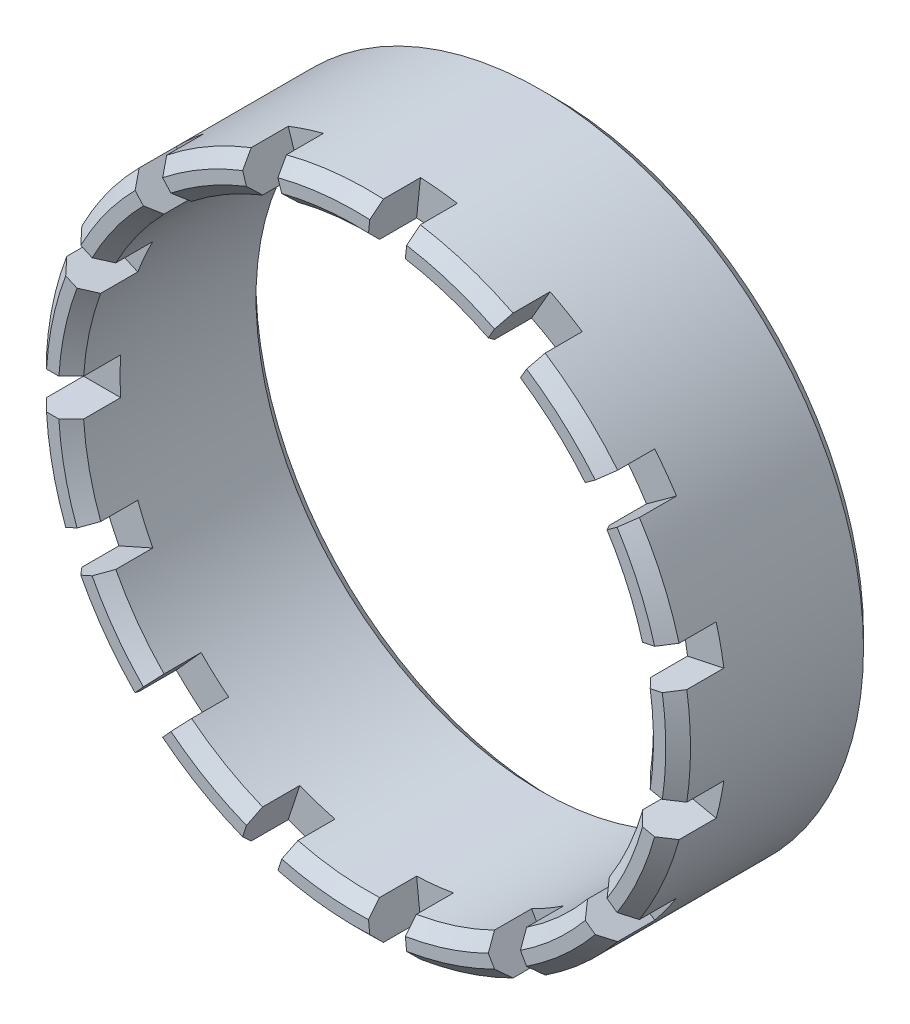
SolidWorks part; units mm, degrees
material "PET"
ref_plane "Front Plane" through (0, 0, 0) normal (0, 0, 1) x (1, 0, 0)
ref_plane "Top Plane" through (0, 0, 0) normal (0, 1, 0) x (1, 0, 0)
ref_plane "Right Plane" through (0, 0, 0) normal (1, 0, 0) x (0, 0, -1)
sketch "Sketch1" plane through (0, 0, 0) normal (0, 0, 1) x (1, 0, 0)
  circle A1 centre (0, 0) radius 36.6395
  circle A2 centre (0, 0) radius 41.402
  dimension "D1" = 4.7625
extrude "Boss-Extrude1" add sketch "Sketch1" against normal blind 25.4
chamfer "Chamfer1" distance 1.5875 angle 45 4 edges at (36.6395, 0, 0) (36.6395, 0, -25.4) (41.402, 0, 0) (41.402, 0, -25.4)
sketch "Sketch2" plane through (0, 0, 0) normal (1, 0, 0) x (0, 0, -1)
  line L0 (0, 39.8145) -> (0, -39.8145) construction
  line L1 (-6.35, -2.3813) -> (6.35, -2.3813)
  line L2 (-6.35, -2.3813) -> (-6.35, 2.3813)
  line L3 (-6.35, 2.3813) -> (6.35, 2.3813)
  line L4 (6.35, -2.3813) -> (6.35, 2.3813)
  line L5 (-6.35, -2.3813) -> (6.35, 2.3813) construction
  line L6 (-6.35, 2.3813) -> (6.35, -2.3813) construction
  point P0 (0, 0)
  dimension "D1" = 4.7625
  dimension "D2" = 6.35
extrude "Cut-Extrude1" cut sketch "Sketch2" against normal through all
fillet "Fillet1" [suppressed] radius 1.5875
pattern_circular "CirPattern1" count 15 over 360 about axis through (0, 0, 0) along (0, 0, 1) of "Fillet1", "Cut-Extrude1"
